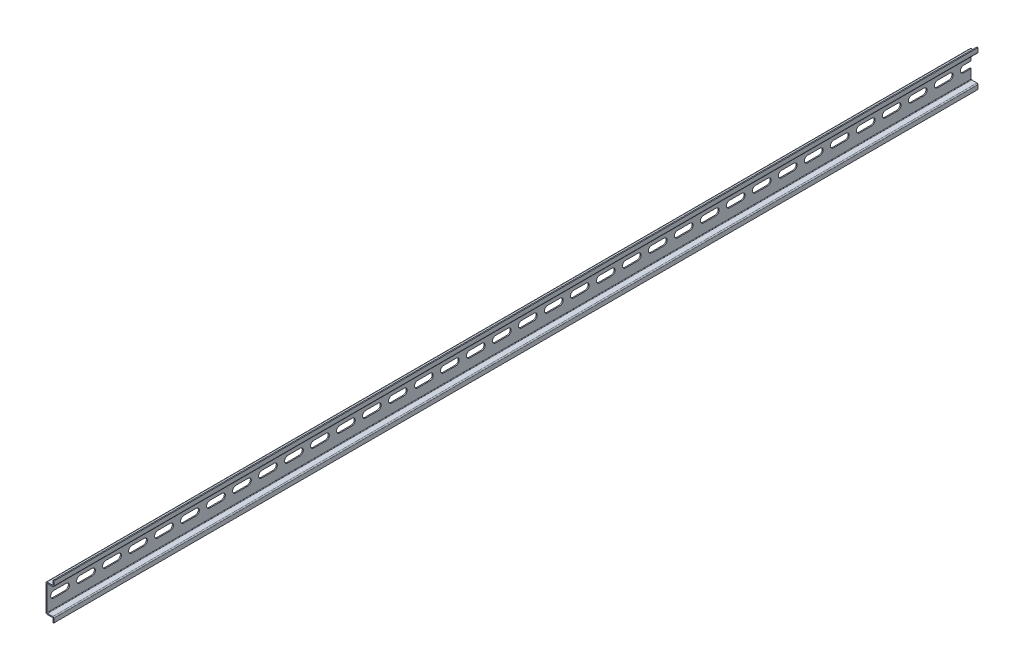
SolidWorks part; units mm, degrees
ref_plane "Front Plane" through (0, 0, 0) normal (0, 0, 1) x (1, 0, 0)
ref_plane "Top Plane" through (0, 0, 0) normal (0, 1, 0) x (1, 0, 0)
ref_plane "Right Plane" through (0, 0, 0) normal (1, 0, 0) x (0, 0, -1)
sketch "Sketch1" plane through (0, 0, 0) normal (0, 0, 1) x (1, 0, 0)
  line L0 (0, 0) -> (7.5, 0) construction
  line L1 (0, 17.5) -> (7.5, 17.5) construction
  line L2 (0, 17.5) -> (0, -17.5) construction
  line L3 (0, -17.5) -> (7.5, -17.5) construction
  line L4 (7.5, 17.5) -> (7.5, -17.5) construction
  line L5 (7.5, 17.5) -> (6.5, 17.5)
  line L6 (6.5, 17.5) -> (6.5, 14)
  line L7 (6, 13.5) -> (1, 13.5)
  line L8 (0, 12.5) -> (0, -12.5)
  line L9 (7.5, 17.5) -> (7.5, 13.5)
  line L10 (6.5, 12.5) -> (1.5, 12.5)
  line L11 (1, 12) -> (1, -12)
  line L12 (6.5, -12.5) -> (1.5, -12.5)
  line L13 (7.5, -17.5) -> (7.5, -13.5)
  line L14 (6, -13.5) -> (1, -13.5)
  line L15 (6.5, -17.5) -> (6.5, -14)
  line L16 (7.5, -17.5) -> (6.5, -17.5)
  line L17 (6.3536, 13.6464) -> (7.2071, 12.7929) construction
  line L18 (1.1464, 12.3536) -> (0.2929, 13.2071) construction
  arc A0 (1.5, 12.5) -> (1, 12) centre (1.5, 12) ccw
  arc A1 (1, 13.5) -> (0, 12.5) centre (1, 12.5) ccw
  arc A2 (7.5, 13.5) -> (6.5, 12.5) centre (6.5, 13.5) cw
  arc A3 (6, 13.5) -> (6.5, 14) centre (6, 14) ccw
  arc A4 (1, -13.5) -> (0, -12.5) centre (1, -12.5) cw
  arc A5 (1.5, -12.5) -> (1, -12) centre (1.5, -12) cw
  arc A6 (7.5, -13.5) -> (6.5, -12.5) centre (6.5, -13.5) ccw
  arc A7 (6, -13.5) -> (6.5, -14) centre (6, -14) cw
  dimension "D5" = 1
  dimension "D6" = 0.5
  dimension "D1" = 35
  dimension "D2" = 7.5
  dimension "D3" = 1
  dimension "D4" = 27
extrude "Boss-Extrude1" add sketch "Sketch1" along normal mid plane 889
sketch "Sketch2" plane through (0, 0, 0) normal (1, 0, 0) x (0, 0, -1)
  line L0 (-437.85, 0) -> (-426.15, 0) construction
  line L1 (-437.85, 3.15) -> (-426.15, 3.15)
  line L2 (-437.85, -3.15) -> (-426.15, -3.15)
  line L3 (-432, 0) -> (-444.5, 0) construction
  line L4 (-444.5, 12.5) -> (-444.5, -12.5) construction
  line L5 (-432, 0) -> (-407, 0) construction
  line L6 (-407, 0) -> (-382, 0) construction
  arc A0 (-437.85, 3.15) -> (-437.85, -3.15) centre (-437.85, 0) ccw
  arc A1 (-426.15, -3.15) -> (-426.15, 3.15) centre (-426.15, 0) ccw
  point P2 (-432, 0)
  dimension "D1" = 6.3
extrude "Cut-Extrude1" cut sketch "Sketch2" along normal up to vertex (7.5 mm away) up to point (7.5, 0, 0)
pattern_linear "LPattern1" count 36 spacing 25 along (0, 0, -1) of "Cut-Extrude1"
equation "\"D4@Sketch2\" = \"D3@Sketch2\" / 2"
equation "\"D3@LPattern1\" = \"D3@Sketch2\""
equation "\"D1@LPattern1\" = \"D1@Boss-Extrude1\" / \"D3@LPattern1\""
